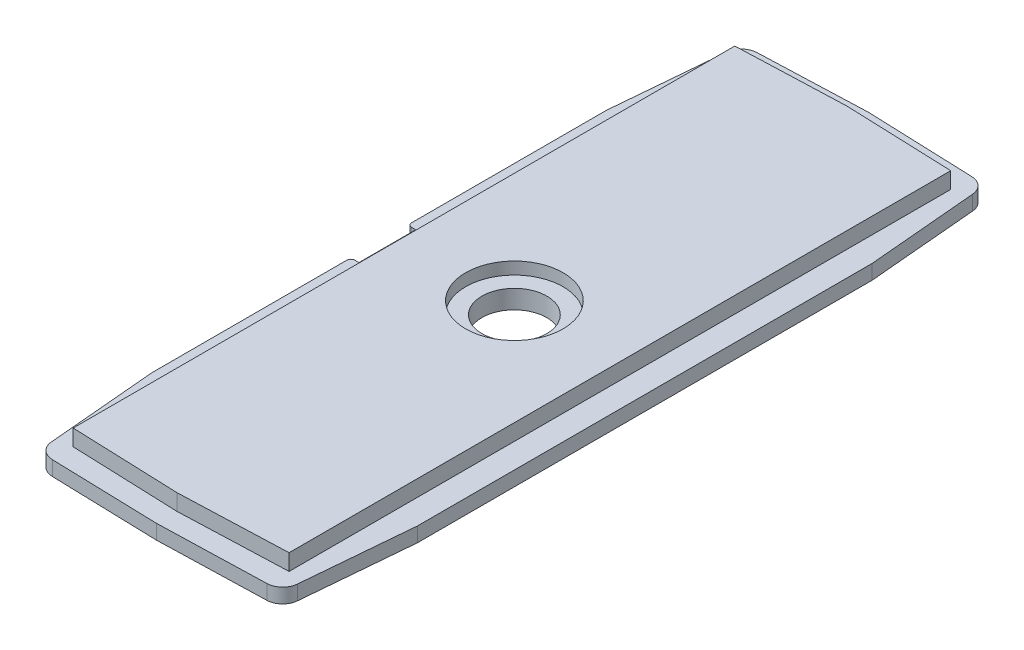
SolidWorks part; units mm, degrees
ref_plane "Спереди" through (0, 0, 0) normal (0, 0, 1) x (1, 0, 0)
ref_plane "Сверху" through (0, 0, 0) normal (0, 1, 0) x (1, 0, 0)
ref_plane "Справа" through (0, 0, 0) normal (1, 0, 0) x (0, 0, -1)
sketch "Эскиз1" plane through (0, 0, 0) normal (0, 1, 0) x (1, 0, 0)
  line L0 (-15, 43.3494) -> (-16.35, 28)
  line L1 (-16.35, 0) -> (16.35, 0) construction
  line L2 (-15.35, 3.5) -> (-15.35, -3.5)
  line L3 (-15.35, -3.5) -> (-15.85, -3.5)
  line L4 (-15.35, 3.5) -> (-15.85, 3.5)
  line L5 (-15, -43.3506) -> (0, -43.7847)
  line L6 (0, -43.7847) -> (15, -43.3506)
  line L7 (15, -43.3506) -> (16.35, -28)
  line L8 (15, 43.3494) -> (0, 43.9153)
  line L9 (0, 43.9153) -> (-15, 43.3494)
  line L10 (-16.35, 28) -> (-16.35, 4)
  line L11 (16.35, 28) -> (15, 43.3494)
  line L12 (-16.35, -28) -> (-15, -43.3506)
  line L13 (16.35, -28) -> (16.35, 28)
  line L14 (-16.35, -4) -> (-16.35, -28)
  arc A0 (-16.35, -4) -> (-15.85, -3.5) centre (-15.85, -4) cw
  arc A1 (-16.35, 4) -> (-15.85, 3.5) centre (-15.85, 4) ccw
  point P20 (-16.35, -3.5)
  dimension "D7" = 0.5
  dimension "D1" = 32.7
  dimension "D2" = 15
  dimension "D3" = 87.7
  dimension "D4" = 56
  dimension "D5" = 7
  dimension "D6" = 15
  dimension "D8" = 1
extrude "Бобышка-Вытянуть1" add sketch "Эскиз1" along normal blind 1.8
sketch "Эскиз4" plane through (0, 0, 0) normal (0, 1, 0) x (1, 0, 0)
  line L0 (-13.3, 40.75) -> (-13.3, -40.75)
  line L1 (-13.3, -40.75) -> (0, -41.25)
  line L2 (0, -41.25) -> (13.3, -40.75)
  line L3 (13.3, -40.75) -> (13.3, 40.75)
  line L4 (13.3, 40.75) -> (0, 41.25)
  line L5 (0, 41.25) -> (-13.3, 40.75)
  line L6 (-13.3, 0) -> (13.3, 0) construction
  dimension "D1" = 26.6
  dimension "D2" = 82.5
  dimension "D3" = 81.5
extrude "Бобышка-Вытянуть2" add sketch "Эскиз4" along normal blind 3.8
fillet "Скругление1" radius 2 4 edges at (15, 0.9, 43.3506) (-15, 0.9, 43.3506) (-15, 0.9, -43.3494) (15, 0.9, -43.3494)
sketch "Эскиз5" plane through (0, 3.8, 0) normal (0, 1, 0) x (-1, 0, 0)
  line L1 (-13.3, 40.75) -> (-13.3, -40.75) construction
  line L2 (3.7, 0) -> (-4.3, 0) construction
  line L3 (-0.3, -4) -> (-0.3, 4) construction
  circle A0 centre (-0.3, 0) radius 4
  point P8 (-13.3, 0)
  dimension "D1" = 8
  dimension "D2" = 13
extrude "Вырез-Вытянуть1" cut sketch "Эскиз5" against normal blind 4
sketch "Эскиз6" plane through (0, 3.8, 0) normal (0, 1, 0) x (1, 0, 0)
  line L0 (13.3, -40.75) -> (13.3, 40.75) construction
  circle A0 centre (0.3, 0) radius 6
  point P2 (13.3, 0)
  dimension "D1" = 12
  dimension "D2" = 13
extrude "Вырез-Вытянуть2" cut sketch "Эскиз6" against normal blind 1.5
sketch "Эскиз7" plane through (0, 3.8, 0) normal (0, 1, 0) x (-1, 0, 0)
  line L0 (-13.3, 40.75) -> (-13.3, -40.75) construction
  line L1 (5.2, -5) -> (-6.8, -5)
  line L2 (5.2, -5) -> (5.2, 5)
  line L3 (5.2, 5) -> (-6.8, 5)
  line L4 (-6.8, -5) -> (-6.8, 5)
  line L5 (5.2, 0) -> (-6.8, 0) construction
  point P4 (-13.3, 0)
  dimension "D1" = 10
  dimension "D2" = 12
  dimension "D3" = 6.5
extrude "Вырез-Вытянуть3" [suppressed] cut sketch "Эскиз7" against normal blind 4
